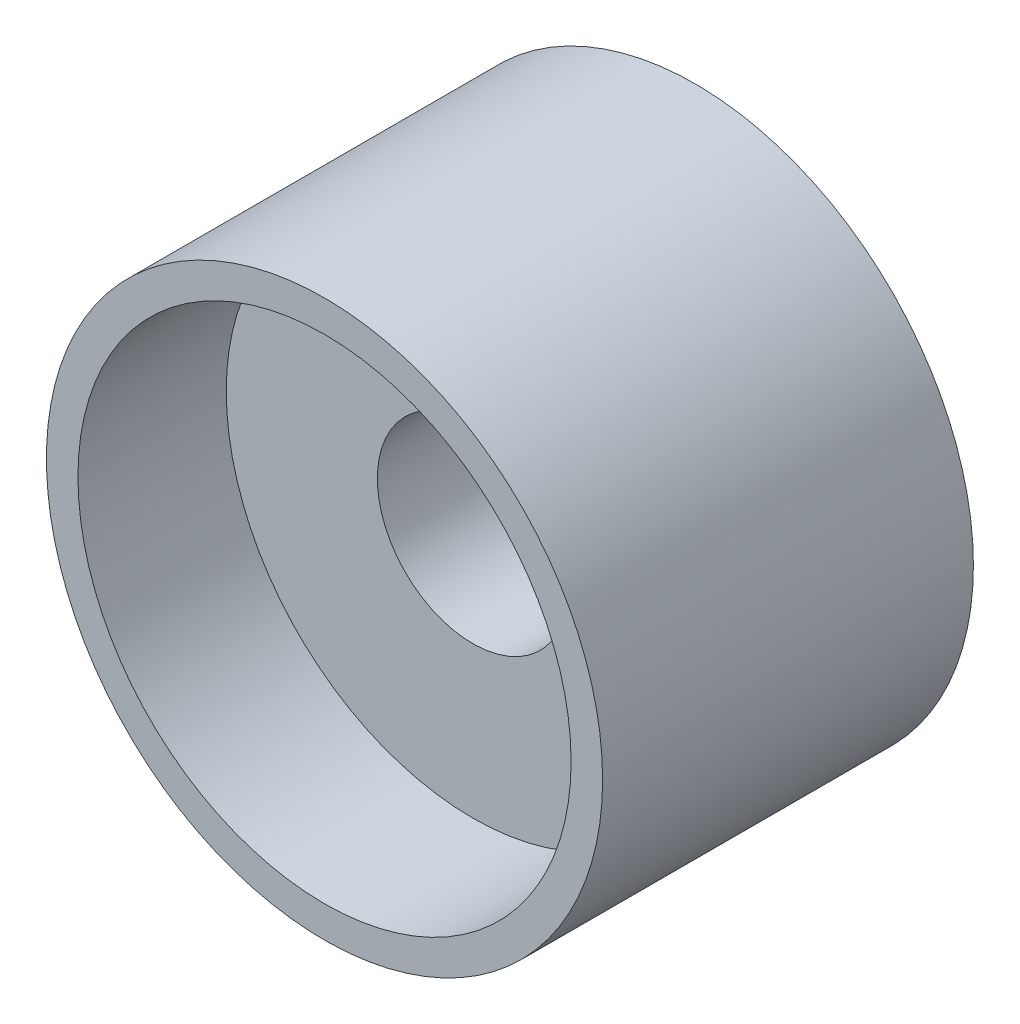
SolidWorks part; units mm, degrees
ref_plane "Front Plane" through (0, 0, 0) normal (0, 0, 1) x (1, 0, 0)
ref_plane "Top Plane" through (0, 0, 0) normal (0, 1, 0) x (1, 0, 0)
ref_plane "Right Plane" through (0, 0, 0) normal (1, 0, 0) x (0, 0, -1)
sketch "Sketch1" plane through (0, 0, 0) normal (0, 0, 1) x (1, 0, 0)
  circle A0 centre (0, 0) radius 15
  circle A1 centre (0, 0) radius 5.15
  dimension "D1" = 30
  dimension "D2" = 10.3
extrude "Boss-Extrude1" add sketch "Sketch1" along normal blind 20
sketch "Sketch2" plane through (0, 0, 20) normal (0, 0, 1) x (1, 0, 0)
  circle A0 centre (0, 0) radius 13.3
  circle A1 centre (0, 0) radius 15 construction
  dimension "D1" = 1.7
extrude "Cut-Extrude1" cut sketch "Sketch2" against normal blind 8
